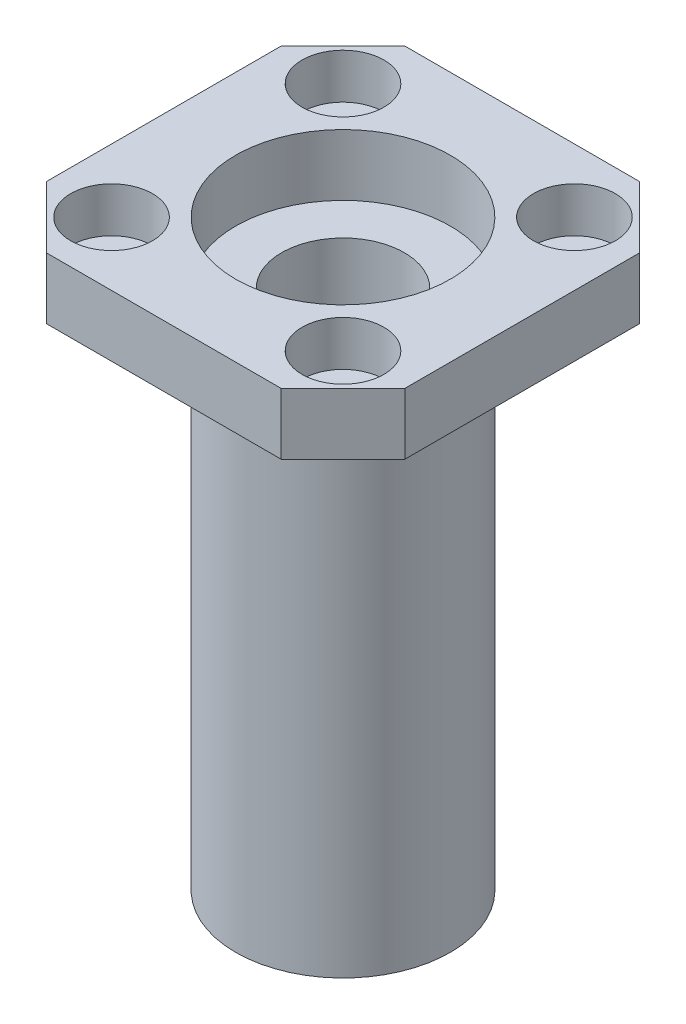
SolidWorks part; units mm, degrees
ref_plane "Front Plane" through (0, 0, 0) normal (0, 0, 1) x (1, 0, 0)
ref_plane "Top Plane" through (0, 0, 0) normal (0, 1, 0) x (1, 0, 0)
ref_plane "Right Plane" through (0, 0, 0) normal (1, 0, 0) x (0, 0, -1)
sketch "Sketch1" plane through (0, 0, 0) normal (0, 1, 0) x (1, 0, 0)
  circle A0 centre (0, 0) radius 6
  circle A1 centre (0, 0) radius 10.5
  dimension "D1" = 12
  dimension "D2" = 21
extrude "Boss-Extrude1" add sketch "Sketch1" along normal blind 51
sketch "Sketch2" plane through (0, 51, 0) normal (0, 1, 0) x (1, 0, 0)
  line L0 (-17.5165, -11.4748) -> (-11.4748, -17.5165)
  line L1 (-17.5165, 17.5165) -> (17.5165, 17.5165)
  line L2 (-17.5165, 17.5165) -> (-17.5165, -17.5165)
  line L3 (-17.5165, -17.5165) -> (17.5165, -17.5165)
  line L4 (17.5165, 17.5165) -> (17.5165, -17.5165)
  line L5 (-17.5165, 17.5165) -> (17.5165, -17.5165) construction
  line L6 (-17.5165, -17.5165) -> (17.5165, 17.5165) construction
  line L7 (11.4748, 17.5165) -> (17.5165, 11.4748)
  line L8 (-17.5165, 11.4748) -> (-11.4748, 17.5165)
  line L9 (11.4748, -17.5165) -> (17.5165, -11.4748)
  circle A0 centre (0, 0) radius 16
  circle A1 centre (-11.3137, 11.3137) radius 2.25
  circle A2 centre (-11.3137, -11.3137) radius 2.25
  circle A3 centre (11.3137, -11.3137) radius 2.25
  circle A4 centre (11.3137, 11.3137) radius 2.25
  point P0 (0, 0)
  circle M9 centre (0, 0) radius 10.5
  dimension "D1" = 32
  dimension "D2" = 4.5
  dimension "D3" = 41
  dimension "D4" = 41
  dimension "D5" = 20.5
  dimension "D6" = 20.5
extrude "Boss-Extrude2" add sketch "Sketch2" along normal blind 6 separate body contours L3 L9 L4 L7 L1 L8 L2 L0 A4 A0 A3 A2 A1 | A4 A0 A1 A2 A3 M9
sketch "Sketch3" plane through (0, 57, 0) normal (0, 1, 0) x (1, 0, 0)
  circle A0 centre (-11.3137, 11.3137) radius 4
  circle A1 centre (-11.3137, -11.3137) radius 4
  circle A2 centre (11.3137, -11.3137) radius 4
  circle A3 centre (11.3137, 11.3137) radius 4
  dimension "D1" = 8
extrude "Cut-Extrude1" cut sketch "Sketch3" against normal blind 4.4
